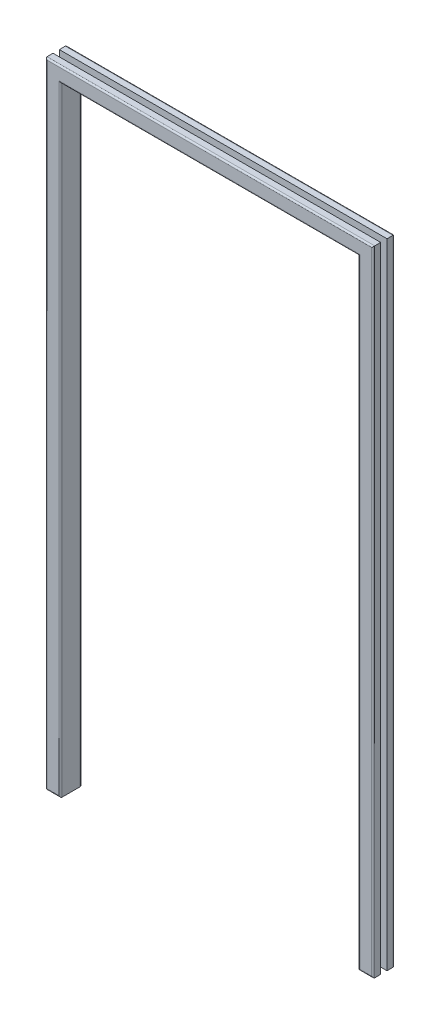
SolidWorks part; units mm, degrees
ref_plane "Front Plane" through (0, 0, 0) normal (0, 0, 1) x (1, 0, 0)
ref_plane "Top Plane" through (0, 0, 0) normal (0, 1, 0) x (1, 0, 0)
ref_plane "Right Plane" through (0, 0, 0) normal (1, 0, 0) x (0, 0, -1)
sketch "Sketch1" plane through (0, 0, 0) normal (0, 0, 1) x (1, 0, 0)
  line L1 (0, 0) -> (1117.6, 0)
  line L2 (0, 0) -> (0, 2162.175)
  line L3 (0, 2162.175) -> (1117.6, 2162.175)
  line L4 (1117.6, 0) -> (1117.6, 2162.175)
  dimension "D1" = 2162.175
  dimension "D2" = 1117.6
extrude "Boss-Extrude1" add sketch "Sketch1" along normal blind 25.4
sketch "Sketch6" plane through (0, 0, 0) normal (0, 0, -1) x (-1, 0, 0)
  line L0 (-1066.8, 0) -> (-1092.2, 0)
  line L1 (0, 0) -> (-1117.6, 0) construction
  line L2 (-1092.2, 0) -> (-1092.2, 2136.775)
  line L3 (-1092.2, 2136.775) -> (-25.4, 2136.775)
  line L4 (-25.4, 2136.775) -> (-25.4, 0)
  line L5 (-25.4, 0) -> (-50.8, 0)
  line L6 (-50.8, 2111.375) -> (-1066.8, 2111.375)
  line L7 (-1066.8, 2111.375) -> (-1066.8, 0)
  line L8 (-50.8, 2111.375) -> (-50.8, 0)
  line L9 (-1117.6, 0) -> (-1117.6, 2162.175) construction
  line L10 (0, 2162.175) -> (0, 0) construction
  line L11 (-1117.6, 2162.175) -> (0, 2162.175) construction
  dimension "D1" = 25.4
  dimension "D2" = 25.4
  dimension "D3" = 25.4
  dimension "D4" = 25.4
  dimension "D5" = 25.4
extrude "Boss-Extrude4" add sketch "Sketch6" along normal blind 21.59
sketch "Sketch7" plane through (0, 0, -21.59) normal (0, 0, -1) x (-1, 0, 0)
  line L1 (-1117.6, 2162.175) -> (0, 2162.175)
  line L2 (-1117.6, 2162.175) -> (-1117.6, 0)
  line L3 (-1117.6, 0) -> (0, 0)
  line L4 (0, 2162.175) -> (0, 0)
extrude "Boss-Extrude5" add sketch "Sketch7" along normal blind 25.4
sketch "Sketch8" plane through (0, 0, 25.4) normal (0, 0, 1) x (1, 0, 0)
  line L0 (0, 0) -> (1117.6, 0) construction
  line L1 (50.8, 0) -> (1066.8, 0)
  line L2 (50.8, 0) -> (50.8, 2111.375)
  line L3 (50.8, 2111.375) -> (1066.8, 2111.375)
  line L4 (1066.8, 0) -> (1066.8, 2111.375)
  line L5 (1117.6, 0) -> (1117.6, 2162.175) construction
  line L6 (0, 2162.175) -> (0, 0) construction
  dimension "D1" = 2111.375
  dimension "D2" = 50.8
  dimension "D3" = 50.8
  dimension "D4" = 1016
extrude "Cut-Extrude2" cut sketch "Sketch8" against normal through all
fillet "Fillet1" radius 5.08 15 edges at (558.8, 2111.375, -46.99) (1066.8, 1055.6875, -46.99) (1092.2, 0, -46.99) (1117.6, 1081.0875, -46.99) (558.8, 2162.175, -46.99) (0, 1081.0875, -46.99) (25.4, 0, -46.99) (50.8, 1055.6875, -46.99) (0, 1081.0875, 25.4) (558.8, 2162.175, 25.4) (1117.6, 1081.0875, 25.4) (25.4, 0, 25.4) (1066.8, 1055.6875, 25.4) (558.8, 2111.375, 25.4) (50.8, 1055.6875, 25.4)
